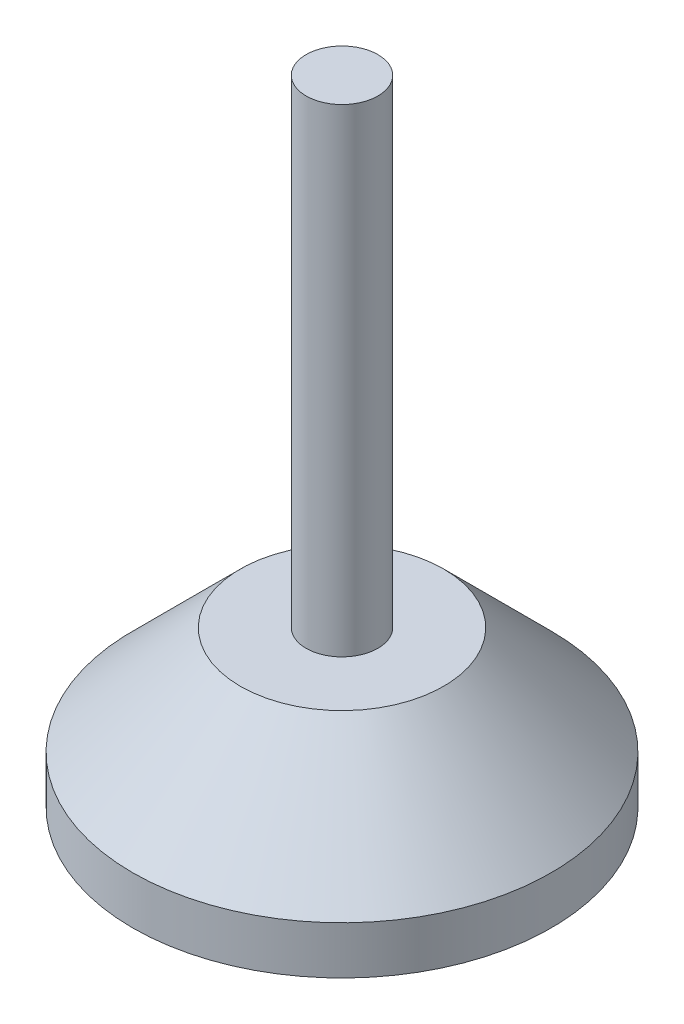
SolidWorks part; units mm, degrees
ref_plane "Front Plane" through (0, 0, 0) normal (0, 0, 1) x (1, 0, 0)
ref_plane "Top Plane" through (0, 0, 0) normal (0, 1, 0) x (1, 0, 0)
ref_plane "Right Plane" through (0, 0, 0) normal (1, 0, 0) x (0, 0, -1)
sketch "Sketch1" plane through (0, 0, 0) normal (1, 0, 0) x (0, 0, -1)
  line L0 (0, 0) -> (27.7812, 0)
  line L1 (27.7812, 0) -> (27.7812, 6.35)
  line L2 (27.7812, 6.35) -> (13.4937, 20.6375)
  line L3 (13.4937, 20.6375) -> (4.7625, 20.6375)
  line L4 (4.7625, 20.6375) -> (4.7625, 84.1375)
  line L5 (4.7625, 84.1375) -> (0, 84.1375)
  line L6 (0, 0.7457) -> (0, 50000.7457) construction
  line L7 (0, 0) -> (0, 84.1375)
  dimension "D1" = 9.525
  dimension "D2" = 63.5
  dimension "D3" = 45
  dimension "D4" = 55.5625
  dimension "D5" = 84.1375
  dimension "D6" = 6.35
revolve "Revolve1" add sketch "Sketch1" angle 360 about L6
